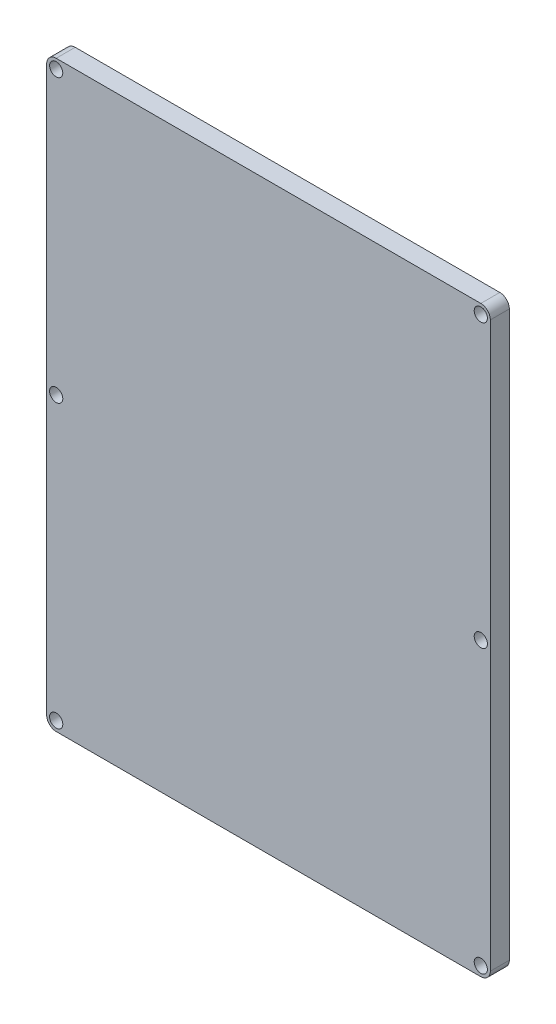
SolidWorks part; units mm, degrees
ref_plane "Front Plane" through (0, 0, 0) normal (0, 0, 1) x (1, 0, 0)
ref_plane "Top Plane" through (0, 0, 0) normal (0, 1, 0) x (1, 0, 0)
ref_plane "Right Plane" through (0, 0, 0) normal (1, 0, 0) x (0, 0, -1)
sketch "Sketch1" plane through (0, 0, 0) normal (0, 0, 1) x (1, 0, 0)
  line L1 (-33.5, 46) -> (33.5, 46)
  line L2 (-35, 44.5) -> (-35, -44.5)
  line L3 (-33.5, -46) -> (33.5, -46)
  line L4 (35, 44.5) -> (35, -44.5)
  line L5 (-35, 46) -> (35, -46) construction
  line L6 (-35, -46) -> (35, 46) construction
  arc A0 (33.5, 46) -> (35, 44.5) centre (33.5, 44.5) cw
  arc A1 (35, -44.5) -> (33.5, -46) centre (33.5, -44.5) cw
  arc A2 (-33.5, -46) -> (-35, -44.5) centre (-33.5, -44.5) cw
  arc A3 (-35, 44.5) -> (-33.5, 46) centre (-33.5, 44.5) cw
  point P0 (0, 0)
  dimension "D3" = 1.5
  dimension "D1" = 92
  dimension "D2" = 70
extrude "Boss-Extrude1" add sketch "Sketch1" along normal blind 3
sketch "Sketch2" plane through (0, 0, 3) normal (0, 0, 1) x (1, 0, 0)
  line L0 (-33.5, 46) -> (-33.5, -46) construction
  line L1 (-33.5, -46) -> (33.5, -46) construction
  line L2 (-35, -44.5) -> (35, -44.5) construction
  line L3 (-35, 44.5) -> (35, 44.5) construction
  line L4 (33.5, 46) -> (33.5, -46) construction
  line L5 (0, 46) -> (0, -46) construction
  line L12 (33.5, 46) -> (-33.5, 46) construction
  line L13 (-35, 0) -> (35, 0) construction
  line L14 (-35, 44.5) -> (-35, -44.5) construction
  line L15 (35, -44.5) -> (35, 44.5) construction
  line L34 (-33.5, 22.25) -> (33.5, 22.25) construction
  arc A0 (33.5, -46) -> (35, -44.5) centre (33.5, -44.5) ccw construction
  point P20 (-33.5, 44.5)
  point P21 (33.5, 44.5)
  point P23 (33.5, -44.5)
  point P24 (-33.5, -44.5)
  point P68 (33.5, 0)
  point P69 (-33.5, 0)
  dimension "D3" = 22.25
hole_wizard "Tap Drill for #3-56 Tap1" positions "Sketch4" profile "Sketch5" hole size "#3-56" standard "ANSI Inch" end condition through all
sketch "Sketch4" plane through (0, 0, 0) normal (0, 0, -1) x (-1, 0, 0)
  line L0 (35, 44.5) -> (-35, 44.5) construction
  line L1 (-33.5, 46) -> (-33.5, -46) construction
  point P0 (-33.5, 44.5)
  point P6 (33.5, -44.5)
  point P9 (33.5, 0)
  point P12 (-33.5, 0)
  point P15 (-33.5, -44.5)
  point P18 (33.5, 44.5)
sketch "Sketch5" plane through (33.5, 44.5, 0) normal (1, 0, 0) x (0, 1, 0)
  line L0 (0, 0) -> (0, 3)
  line L1 (0, 3) -> (1.0414, 3)
  line L2 (1.0414, 3) -> (1.0414, 0)
  line L5 (1.0414, 0) -> (0, 0)
  line L11 (0, -6.35) -> (0, 107.95) construction
  dimension "Thru Hole Dia." = 2.0828
  dimension "Thru Hole Depth" = 3
sketch "Sketch7" plane through (0, 0, 0) normal (0, 0, -1) x (-1, 0, 0)
  line L0 (-35, -44.5) -> (-35, 44.5) construction
  line L1 (35, 44.5) -> (35, -44.5) construction
  line L4 (26, 44) -> (-28, 44)
  line L6 (26, -46) -> (-28, -46)
  line L7 (-29, 43) -> (-29, -45)
  line L8 (33.5, -46) -> (-33.5, -46) construction
  line L10 (27, 43) -> (27, -45)
  arc A0 (27, -45) -> (26, -46) centre (26, -45) cw
  arc A1 (-28, -46) -> (-29, -45) centre (-28, -45) cw
  arc A2 (-29, 43) -> (-28, 44) centre (-28, 43) cw
  arc A3 (26, 44) -> (27, 43) centre (26, 43) cw
  point P5 (0, 0)
  point P20 (-29, -46)
  point P23 (-29, 44)
  point P26 (27, 44)
  dimension "D5" = 1
  dimension "D1" = 6
  dimension "D2" = 90
  dimension "D3" = 8
  dimension "D4" = 56
extrude "Cut-Extrude1" cut sketch "Sketch7" against normal blind 0.1
